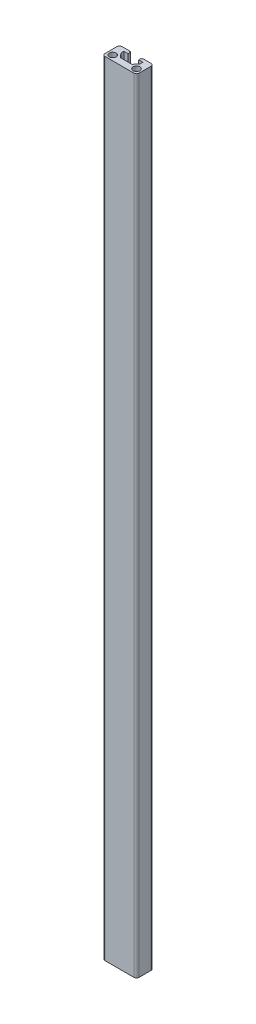
SolidWorks part; units mm, degrees
ref_plane "前视基准面" through (0, 0, 0) normal (0, 0, 1) x (1, 0, 0)
ref_plane "上视基准面" through (0, 0, 0) normal (0, 1, 0) x (1, 0, 0)
ref_plane "右视基准面" through (0, 0, 0) normal (1, 0, 0) x (0, 0, -1)
sketch "草图1" plane through (0, 0, 0) normal (0, 1, 0) x (1, 0, 0)
  line L0 (0, 0) -> (20, 0)
  line L1 (20, 0) -> (20, 10)
  line L2 (20, 10) -> (13.65, 10)
  line L3 (0, 10) -> (0, 0)
  line L4 (6.35, 10) -> (6.35, 9.5104)
  line L5 (6.35, 9.5104) -> (6.9, 9.5104)
  line L6 (6.9, 9.5104) -> (6.9, 8.2)
  line L7 (6.9, 8.2) -> (4.4, 8.2)
  line L8 (4.4, 8.2) -> (4.4, 6.4475)
  line L9 (4.4, 6.4475) -> (6.5873, 3.9)
  line L11 (15.6, 6.4475) -> (15.6, 8.2)
  line L12 (15.6, 8.2) -> (13.1, 8.2)
  line L13 (13.1, 8.2) -> (13.1, 9.5104)
  line L14 (13.1, 9.5104) -> (13.65, 9.5104)
  line L15 (13.65, 9.5104) -> (13.65, 10)
  line L16 (6.35, 10) -> (0, 10)
  line L17 (10, 0) -> (10, 13.7687) construction
  line L18 (6.5873, 3.9) -> (13.4127, 3.9)
  line L19 (13.4127, 3.9) -> (15.6, 6.4475)
  circle A0 centre (3, 3) radius 2
  circle A1 centre (17, 3) radius 2
  point P12 (10, 3.9)
  dimension "D8" = 4
  dimension "D1" = 20
  dimension "D2" = 10
  dimension "D3" = 7.3
  dimension "D4" = 6.2
  dimension "D5" = 1.8
  dimension "D6" = 4.3
  dimension "D7" = 11.2
  dimension "D9" = 3
  dimension "D10" = 14
extrude "凸台-拉伸1" add sketch "草图1" along normal blind 460
fillet "圆角1" radius 1.5 4 edges at (0, 230, -10) (0, 230, 0) (20, 230, -10) (20, 230, 0)
